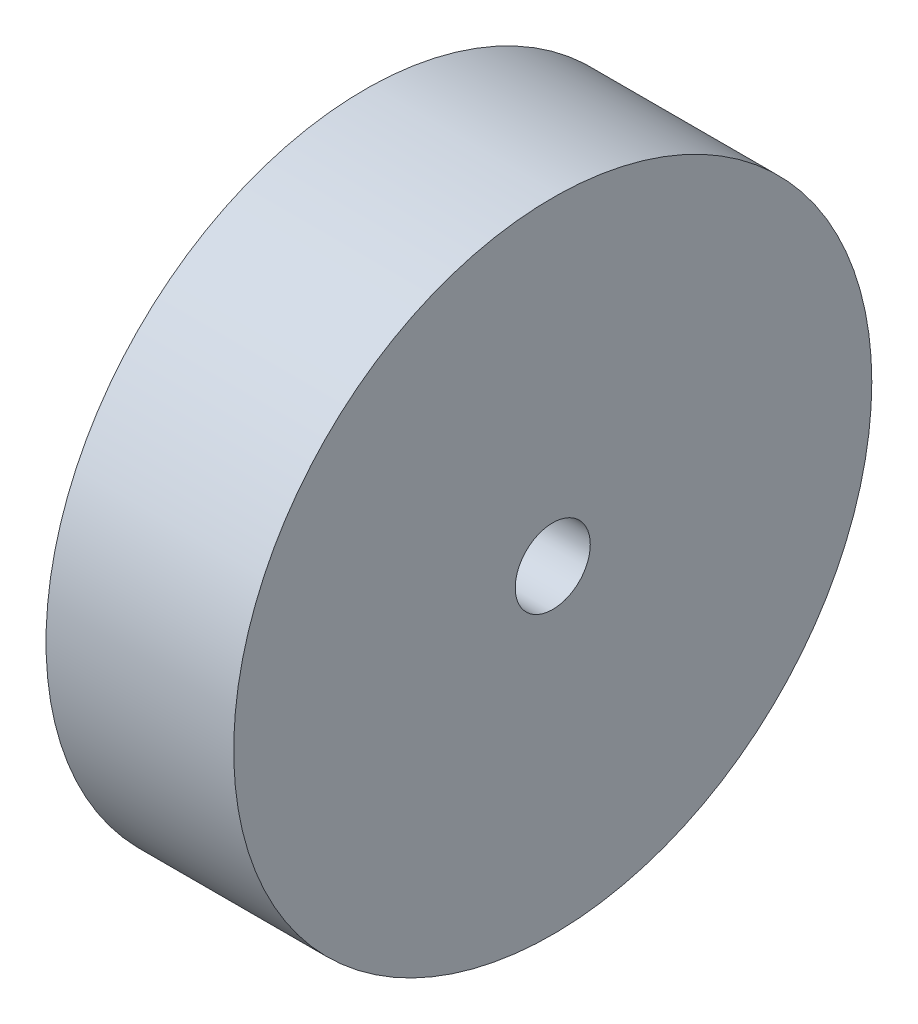
SolidWorks part; units mm, degrees
material "1.4401 (X5CrNiMo17-12-2)"
ref_plane "Plano frontal" through (0, 0, 0) normal (0, 0, 1) x (1, 0, 0)
ref_plane "Plano superior" through (0, 0, 0) normal (0, 1, 0) x (1, 0, 0)
ref_plane "Plano direito" through (0, 0, 0) normal (1, 0, 0) x (0, 0, -1)
sketch "Esboço3" plane through (0, 0, 0) normal (0, 0, 1) x (1, 0, 0)
  line L0 (0, 0) -> (-50.7324, 0) construction
  line L1 (0, 17) -> (0, 2)
  line L2 (-3, 13) -> (-3, 5)
  line L4 (-3, 5) -> (-9, 5)
  line L5 (-9, 5) -> (-9, 2)
  line L6 (-9, 2) -> (0, 2)
  line L7 (-3, 13) -> (-10, 13)
  line L8 (-10, 13) -> (-10, 17)
  line L9 (-10, 17) -> (0, 17)
  dimension "D1" = 2
  dimension "D2" = 17
  dimension "D3" = 4
  dimension "D4" = 6
  dimension "D5" = 5
  dimension "D6" = 3
  dimension "D7" = 10
revolve "Revolução1" add sketch "Esboço3" angle 360 about L0
ref_plane "Plano1" through (0, 5, 0) normal (0, 1, 0) x (1, 0, 0)
hole_wizard "Broca de rosquear para tarraxa de M2.2x0.451" positions "3DSketch6" profile "Esboço11" hole size "M2.2x0.45" standard "DIN"
sketch3d "3DSketch6"
  point P0 (-6, 5, 0)
  dimension "D1" = 3
sketch "Esboço11" plane through (-6, 5, 0) normal (1, 0, 0) x (0, 0, 1)
  line L0 (0, 0) -> (0, 3)
  line L1 (0, 3) -> (0.875, 3)
  line L2 (0.875, 3) -> (0.875, 0)
  line L5 (0.875, 0) -> (0, 0)
  line L11 (0, -6.35) -> (0, 107.95) construction
  dimension "Thru Hole Dia." = 1.75
  dimension "Thru Hole Depth" = 3
